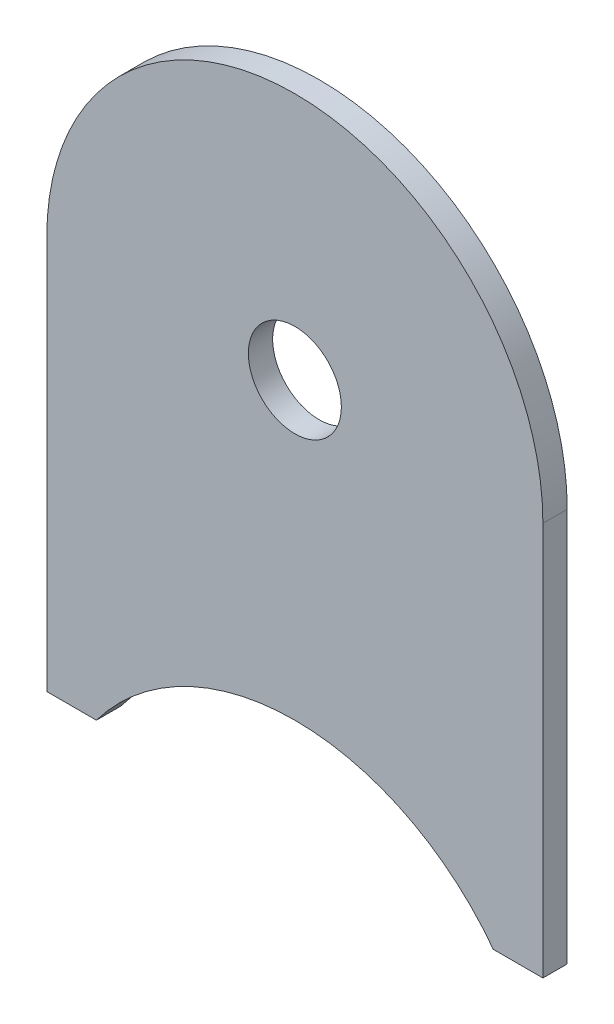
SolidWorks part; units mm, degrees
ref_plane "Front Plane" through (0, 0, 0) normal (0, 0, 1) x (1, 0, 0)
ref_plane "Top Plane" through (0, 0, 0) normal (0, 1, 0) x (1, 0, 0)
ref_plane "Right Plane" through (0, 0, 0) normal (1, 0, 0) x (0, 0, -1)
sketch "Sketch1" plane through (0, 0, 0) normal (0, 0, 1) x (1, 0, 0)
  line L0 (0, 0) -> (2.54, 0)
  line L2 (0, 0) -> (0, 20.1613)
  line L4 (25.4, 0) -> (25.4, 20.1613)
  line L5 (22.86, 0) -> (25.4, 0)
  circle A0 centre (12.7, 20.1613) radius 2.3813
  arc A2 (0, 20.1613) -> (25.4, 20.1613) centre (12.7, 20.1613) cw
  arc A3 (22.86, 0) -> (2.54, 0) centre (12.7, -7.62) ccw
  dimension "D1" = 12.7
  dimension "D2" = 25.4
  dimension "D3" = 4.7625
  dimension "D4" = 7.62
  dimension "D5" = 27.7812
extrude "Boss-Extrude1" add sketch "Sketch1" along normal blind 1.2446
